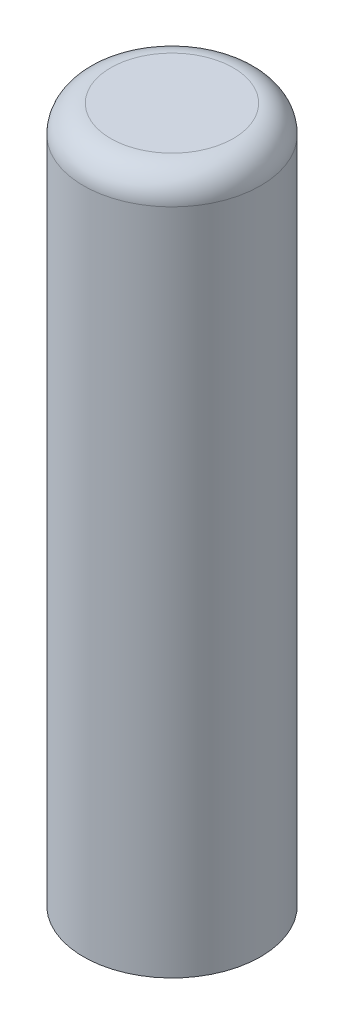
SolidWorks part; units mm, degrees
material "ABS"
ref_plane "Front" through (0, 0, 0) normal (0, 0, 1) x (1, 0, 0)
ref_plane "Top" through (0, 0, 0) normal (0, 1, 0) x (1, 0, 0)
ref_plane "Right" through (0, 0, 0) normal (1, 0, 0) x (0, 0, -1)
sketch "Esquisse1" plane through (0, 0, 0) normal (0, 0, 1) x (1, 0, 0)
  line L0 (0, 0) -> (10, 0)
  line L1 (10, 0) -> (10, -99)
  line L2 (10, -99) -> (9, -99)
  line L3 (9, -99) -> (9, -100)
  line L4 (9, -100) -> (3, -100)
  line L5 (3, -100) -> (3, -10)
  line L6 (3, -10) -> (0, -10)
  line L7 (0, -10) -> (0, 0)
  line L8 (0, -10) -> (0, -100) construction
  line L11 (10.1, 0.1) -> (10.1, -99)
  line L12 (10.1, -99) -> (13, -99)
  line L13 (13, 3) -> (13, -99)
  line L14 (0, 0.1) -> (10.1, 0.1)
  line L15 (0, 0.1) -> (0, 3)
  line L16 (0, 3) -> (13, 3)
  dimension "D1" = 6
  dimension "D2" = 18
  dimension "D3" = 20
  dimension "D4" = 26
  dimension "D5" = 0.1
  dimension "D6" = 90
  dimension "D7" = 100
  dimension "D8" = 1
  dimension "D9" = 0.1
  dimension "D10" = 3
revolve "Révolution1" add sketch "Esquisse1" angle 360 about L8
fillet "Congé1" radius 4 1 edges at (-13, 3, 0)
